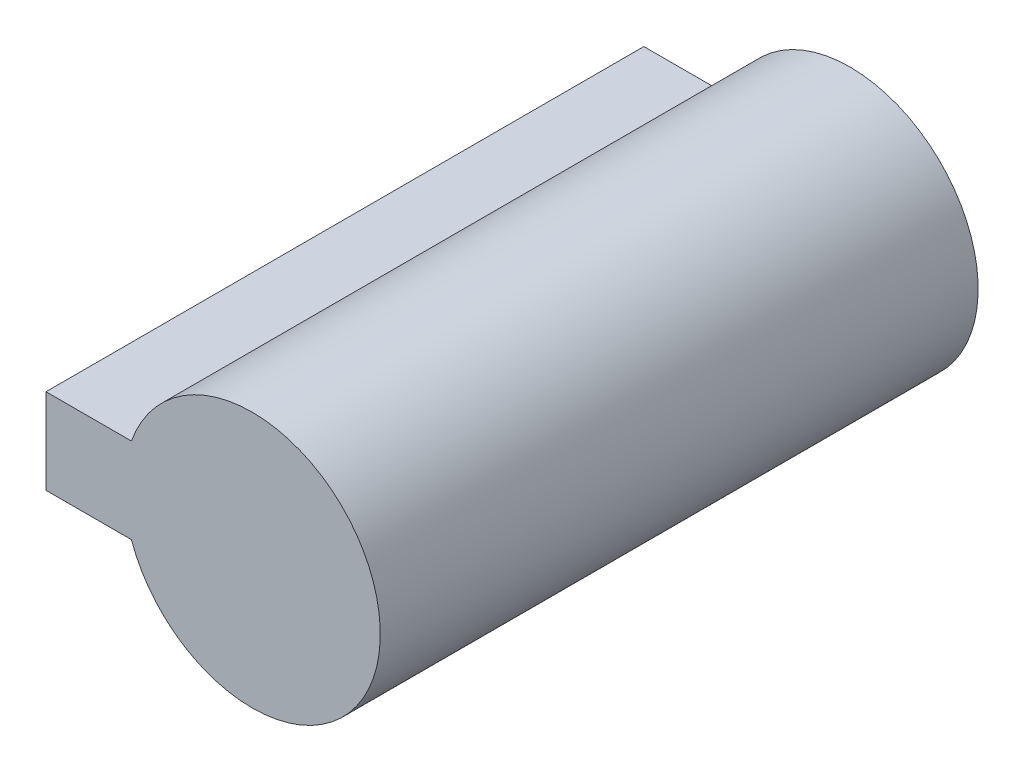
SolidWorks part; units mm, degrees
ref_plane "Front Plane" through (0, 0, 0) normal (0, 0, 1) x (1, 0, 0)
ref_plane "Top Plane" through (0, 0, 0) normal (0, 1, 0) x (1, 0, 0)
ref_plane "Right Plane" through (0, 0, 0) normal (1, 0, 0) x (0, 0, -1)
sketch "Sketch1" plane through (0, 0, 0) normal (0, 0, 1) x (1, 0, 0)
  line L1 (-14.1421, 5) -> (-24.1421, 5)
  line L2 (-24.1421, 5) -> (-24.1421, -5)
  line L3 (-24.1421, -5) -> (-14.1421, -5)
  arc A0 (-14.1421, -5) -> (-14.1421, 5) centre (0, 0) ccw
  dimension "D1" = 30
  dimension "D2" = 10
  dimension "D3" = 10
  dimension "D4" = 24.1421
extrude "Boss-Extrude1" add sketch "Sketch1" along normal blind 70
